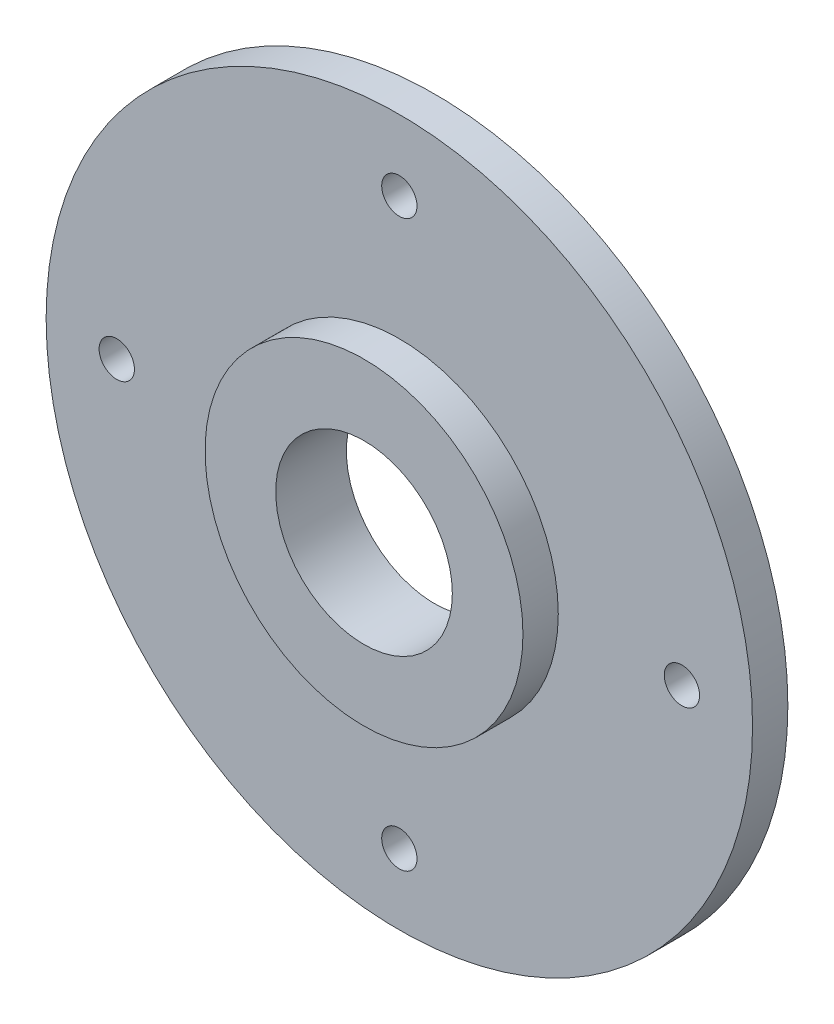
SolidWorks part; units mm, degrees
ref_plane "前视基准面" through (0, 0, 0) normal (0, 0, 1) x (1, 0, 0)
ref_plane "上视基准面" through (0, 0, 0) normal (0, 1, 0) x (1, 0, 0)
ref_plane "右视基准面" through (0, 0, 0) normal (1, 0, 0) x (0, 0, -1)
sketch "草图1" plane through (0, 0, 0) normal (0, 0, 1) x (1, 0, 0)
  circle A0 centre (0, 0) radius 10
  dimension "D1" = 20
extrude "凸台-拉伸1" add sketch "草图1" along normal blind 1
sketch "草图2" plane through (0, 0, 1) normal (0, 0, 1) x (1, 0, 0)
  circle A0 centre (0, 0) radius 4.5
  dimension "D1" = 9
extrude "凸台-拉伸2" add sketch "草图2" along normal blind 1
sketch "草图3" plane through (0, 0, 2) normal (0, 0, 1) x (1, 0, 0)
  circle A0 centre (0, 0) radius 2.5
  dimension "D1" = 5
extrude "切除-拉伸1" cut sketch "草图3" against normal through all
sketch "草图4" plane through (0, 0, 0) normal (0, 0, -1) x (-1, 0, 0)
  circle A0 centre (0, 8) radius 0.5
  circle A1 centre (8, 0) radius 0.5
  circle A2 centre (0, -8) radius 0.5
  circle A3 centre (-8, 0) radius 0.5
  point P12 (0, 0)
  dimension "D1" = 1
  dimension "D2" = 8
  dimension "D3" = 4
extrude "切除-拉伸2" cut sketch "草图4" against normal through all
